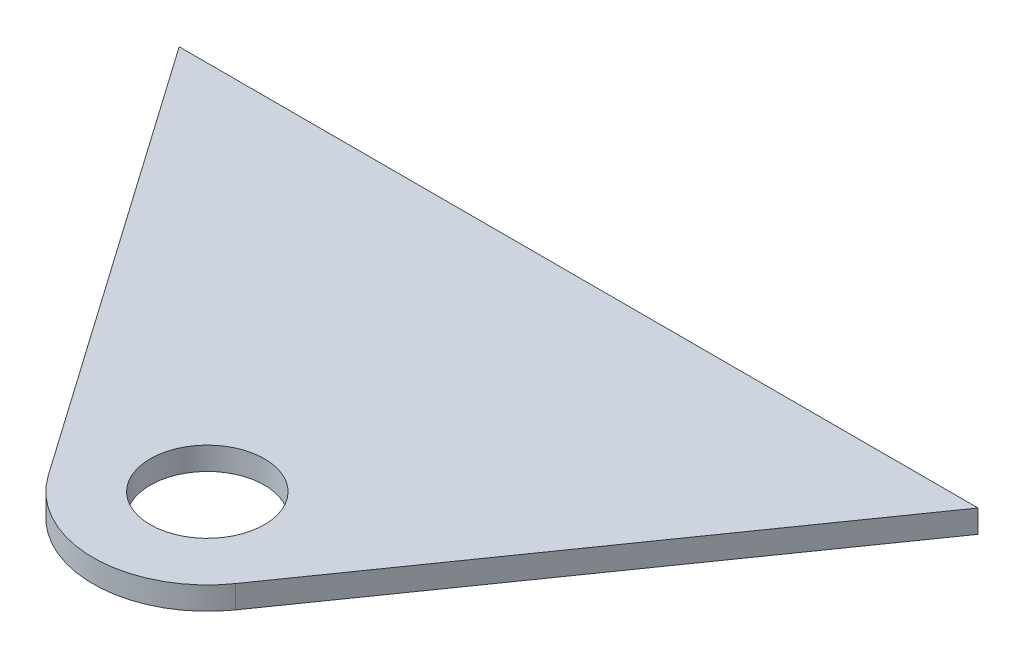
SolidWorks part; units mm, degrees
ref_plane "Front" through (0, 0, 0) normal (0, 0, 1) x (1, 0, 0)
ref_plane "Top" through (0, 0, 0) normal (0, 1, 0) x (1, 0, 0)
ref_plane "Right" through (0, 0, 0) normal (1, 0, 0) x (0, 0, -1)
sketch "Sketch1" plane through (0, 0, 0) normal (0, 1, 0) x (1, 0, 0)
  line L2 (10.4032, -7.2844) -> (44.4049, 41.275)
  line L3 (44.4049, 41.275) -> (-44.4049, 41.275)
  line L4 (-10.4032, -7.2844) -> (-44.4049, 41.275)
  arc A0 (-10.4032, -7.2844) -> (10.4032, -7.2844) centre (0, 0) ccw
  circle A1 centre (0, 0) radius 6.35
  point P0 (0, 0)
  point P4 (12.7, 38.1)
  point P6 (0, 0)
  point P10 (40.804, 38.1)
  point P11 (-12.7, 38.1)
  point P12 (-45.4587, 38.1)
  dimension "D2" = 6.35
  dimension "D3" = 41.275
  dimension "D1" = 12.7
  dimension "D4" = 55
extrude "Boss-Extrude1" add sketch "Sketch1" along normal blind 2.54
